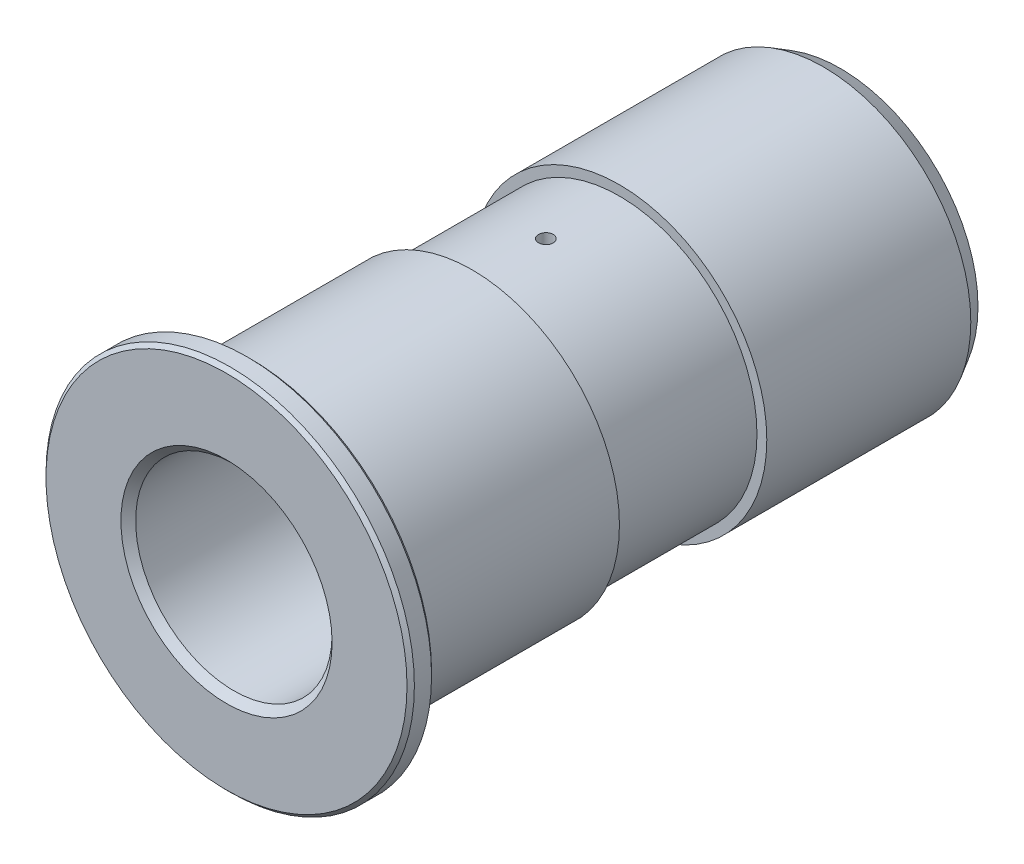
SolidWorks part; units mm, degrees
material "High-leaded brass, UNS C34200"
ref_plane "Front Plane" through (0, 0, 0) normal (0, 0, 1) x (1, 0, 0)
ref_plane "Top Plane" through (0, 0, 0) normal (0, 1, 0) x (1, 0, 0)
ref_plane "Right Plane" through (0, 0, 0) normal (1, 0, 0) x (0, 0, -1)
ref_axis "Axis1" through (0, 0, 84) along (0, 0, -1)
sketch "Sketch1" plane through (0, 0, 0) normal (0, 0, 1) x (1, 0, 0)
  circle A0 centre (0, 0) radius 20
  circle A1 centre (0, 0) radius 30
  dimension "D1" = 60
  dimension "D2" = 40
extrude "Main Body" add sketch "Sketch1" along normal blind 120
sketch "Sketch2" plane through (0, 0, 120) normal (0, 0, 1) x (1, 0, 0)
  circle A0 centre (0, 0) radius 20
  circle A1 centre (0, 0) radius 37.5
  circle A2 centre (0, 0) radius 20 construction
  dimension "D1" = 75
extrude "Boss_Lip" add sketch "Sketch2" along normal blind 5
sketch "Sketch4" plane through (0, 0, 0) normal (0, 1, 0) x (1, 0, 0)
  line L0 (-30, 0) -> (-30, -120) construction
  line L1 (-32, -45) -> (-28, -45)
  line L2 (-32, -45) -> (-32, -75)
  line L3 (-32, -75) -> (-28, -75)
  line L4 (-28, -45) -> (-28, -75)
  line L5 (-32, -45) -> (-28, -75) construction
  line L6 (-32, -75) -> (-28, -45) construction
  point P0 (-30, -60)
  dimension "D1" = 4
  dimension "D2" = 30
revolve "Relief" cut sketch "Sketch4" angle 360 about axis through (0, 0, 84) along (0, 0, -1)
chamfer "Bearling Chamfer" distance 2 angle 60 1 edges at (30, 0, 0)
chamfer "Shaft Chamfer" distance 1.5 angle 45 2 edges at (20, 0, 0) (20, 0, 125)
chamfer "Lip Chamfer" distance 0.75 angle 45 2 edges at (37.5, 0, 120) (37.5, 0, 125)
sketch "Sketch5" plane through (0, 0, 0) normal (0, 1, 0) x (1, 0, 0)
  line L0 (0, -84) -> (0, 4) construction
  line L1 (30, -120) -> (-30, -120) construction
  circle A0 centre (0, -60) radius 1.5
  dimension "D1" = 3
  dimension "D2" = 60
extrude "Cut-Extrude2" cut sketch "Sketch5" along normal up to next
